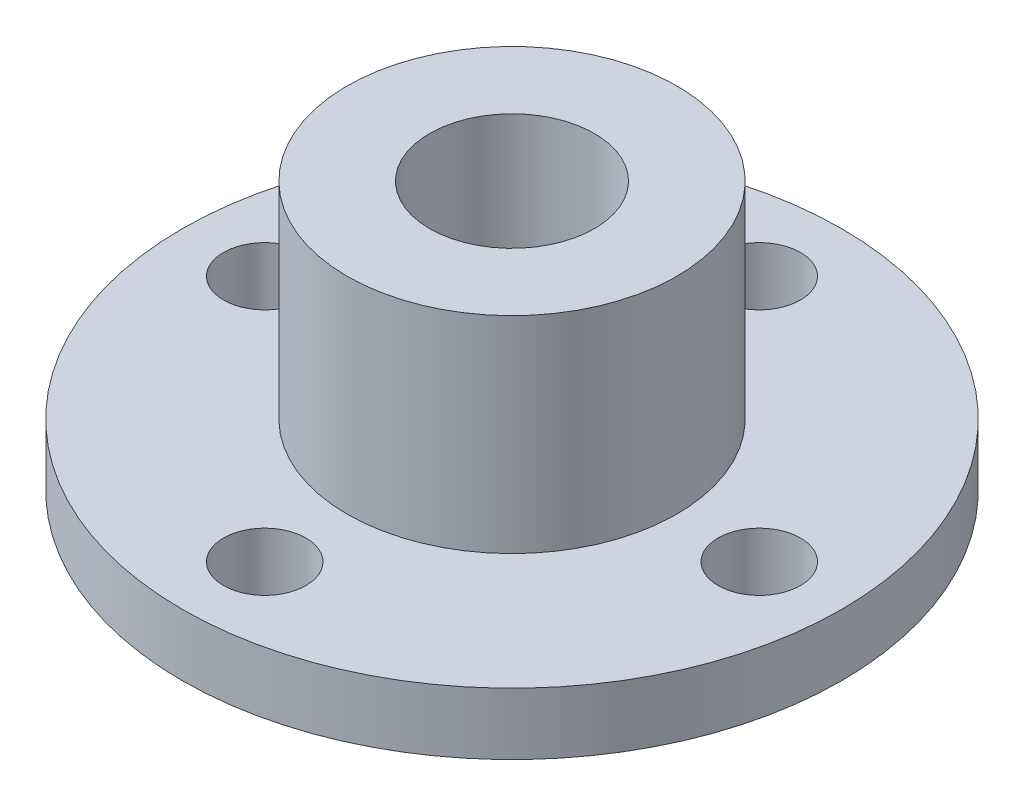
SolidWorks part; units mm, degrees
ref_plane "前视基准面" through (0, 0, 0) normal (0, 0, 1) x (1, 0, 0)
ref_plane "上视基准面" through (0, 0, 0) normal (0, 1, 0) x (1, 0, 0)
ref_plane "右视基准面" through (0, 0, 0) normal (1, 0, 0) x (0, 0, -1)
sketch "草图1" plane through (0, 0, 0) normal (0, 1, 0) x (1, 0, 0)
  circle A0 centre (0, 0) radius 16
  circle A2 centre (0, 12) radius 2
  circle A3 centre (12, 0) radius 2
  circle A4 centre (0, -12) radius 2
  circle A5 centre (-12, 0) radius 2
extrude "凸台-拉伸1" add sketch "草图1" along normal blind 3
sketch "草图2" plane through (0, 3, 0) normal (0, 1, 0) x (1, 0, 0)
  circle A0 centre (0, 0) radius 8
extrude "凸台-拉伸2" add sketch "草图2" along normal blind 10
sketch "草图3" plane through (0, 13, 0) normal (0, 1, 0) x (1, 0, 0)
  circle A0 centre (0, 0) radius 4
  dimension "D1" = 8
extrude "切除-拉伸1" cut sketch "草图3" against normal through all
